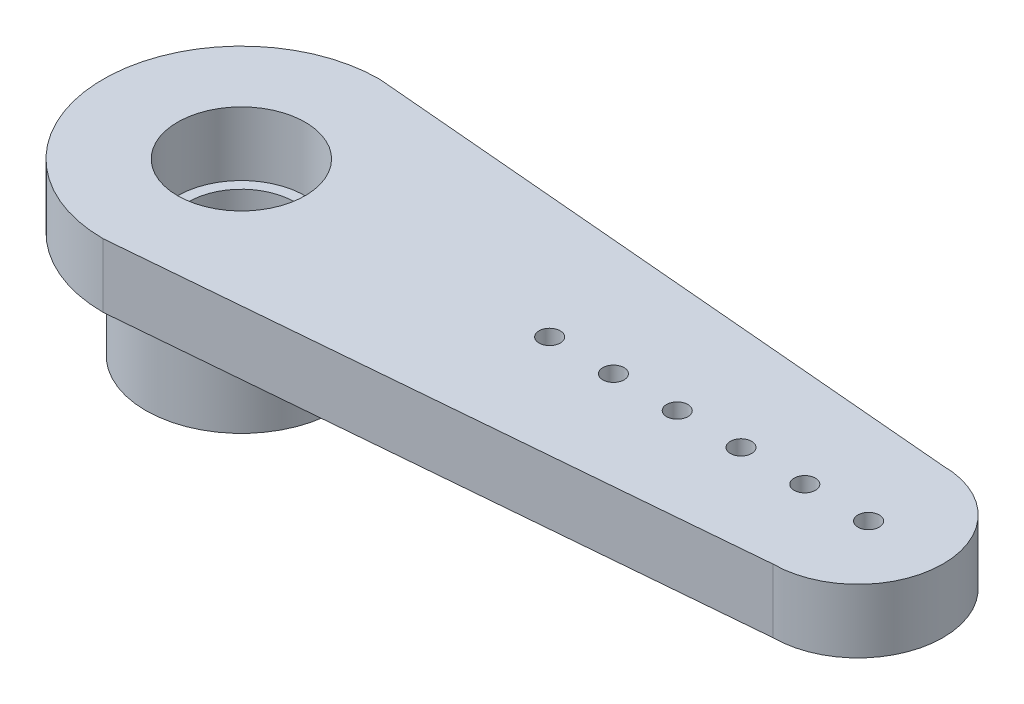
SolidWorks part; units mm, degrees
ref_plane "Front Plane" through (0, 0, 0) normal (0, 0, 1) x (1, 0, 0)
ref_plane "Top Plane" through (0, 0, 0) normal (0, 1, 0) x (1, 0, 0)
ref_plane "Right Plane" through (0, 0, 0) normal (1, 0, 0) x (0, 0, -1)
sketch "Sketch1" plane through (0, 0, 0) normal (0, 1, 0) x (1, 0, 0)
  line L0 (0, 6.5) -> (29, 4)
  line L1 (29, -4) -> (0, -6.5)
  arc A0 (0, 6.5) -> (0, -6.5) centre (0, 0) ccw
  arc A1 (29, -4) -> (29, 4) centre (29, 0) ccw
  circle A2 centre (14.5, 0) radius 0.5
  circle A3 centre (17.5, 0) radius 0.5
  circle A4 centre (20.5, 0) radius 0.5
  circle A5 centre (23.5, 0) radius 0.5
  circle A6 centre (26.5, 0) radius 0.5
  circle A7 centre (29.5, 0) radius 0.5
  dimension "D1" = 13
  dimension "D2" = 8
  dimension "D5" = 1
  dimension "D3" = 29
  dimension "D4" = 14.5
  dimension "D6" = 6
extrude "Boss-Extrude1" add sketch "Sketch1" along normal blind 3
sketch "Sketch3" plane through (0, 0, 0) normal (0, -1, 0) x (1, 0, 0)
  circle A0 centre (0, 0) radius 4.5
  circle A1 centre (0, 0) radius 2.5
  dimension "D1" = 5
  dimension "D2" = 9
extrude "Boss-Extrude2" add sketch "Sketch3" along normal blind 5
sketch "Sketch4" plane through (0, 3, 0) normal (0, 1, 0) x (1, 0, 0)
  circle A0 centre (0, 0) radius 3
  dimension "D1" = 6
extrude "Cut-Extrude1" cut sketch "Sketch4" against normal blind 3
